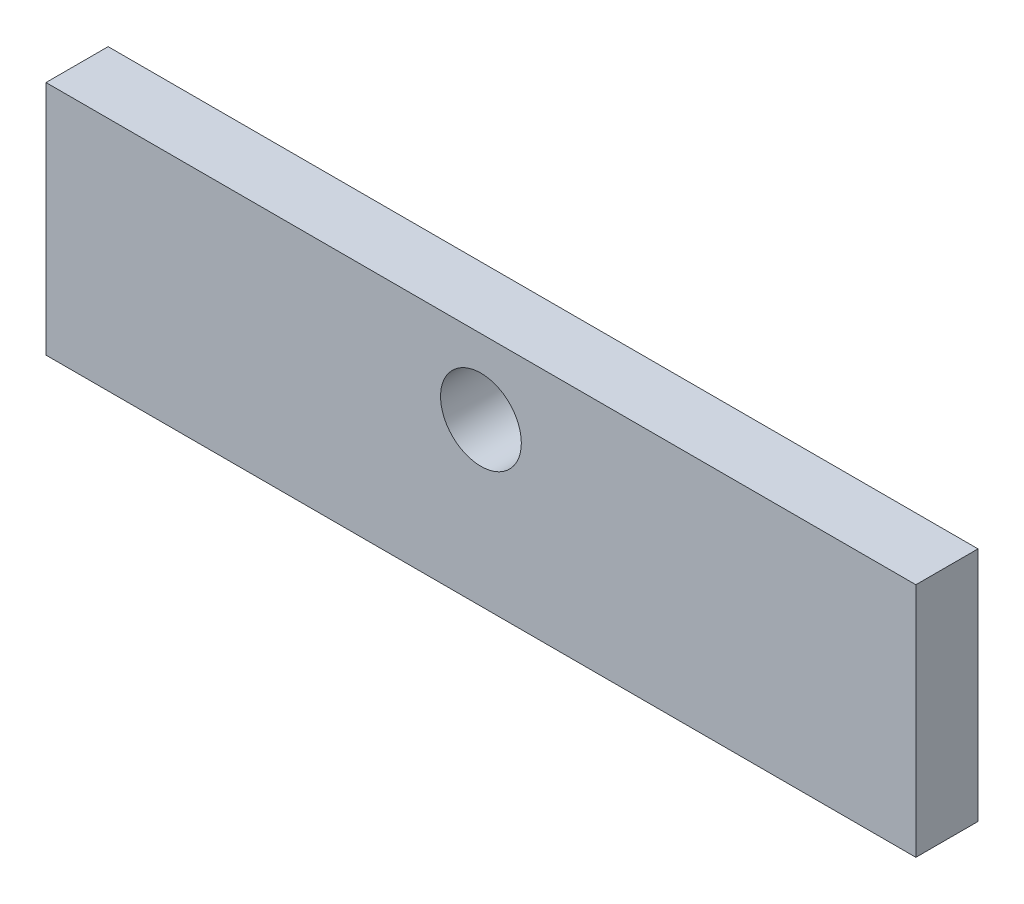
SolidWorks part; units mm, degrees
material "Plain Carbon Steel"
ref_plane "Front Plane" through (0, 0, 0) normal (0, 0, 1) x (1, 0, 0)
ref_plane "Top Plane" through (0, 0, 0) normal (0, 1, 0) x (1, 0, 0)
ref_plane "Right Plane" through (0, 0, 0) normal (1, 0, 0) x (0, 0, -1)
sketch "Sketch1" plane through (0, 0, 0) normal (0, 0, 1) x (1, 0, 0)
  line L0 (-750, 170) -> (750, 170) construction
  line L1 (-350, -20) -> (350, -20)
  line L2 (-350, -20) -> (-350, 170)
  line L3 (-350, 170) -> (350, 170)
  line L4 (350, -20) -> (350, 170)
extrude "Boss-Extrude1" add sketch "Sketch1" along normal blind 50
sketch "Sketch2" plane through (0, 0, 50) normal (0, 0, 1) x (1, 0, 0)
  circle A0 centre (0, 110) radius 32.5
  dimension "D1" = 65
extrude "Cut-Extrude1" cut sketch "Sketch2" against normal up to next
